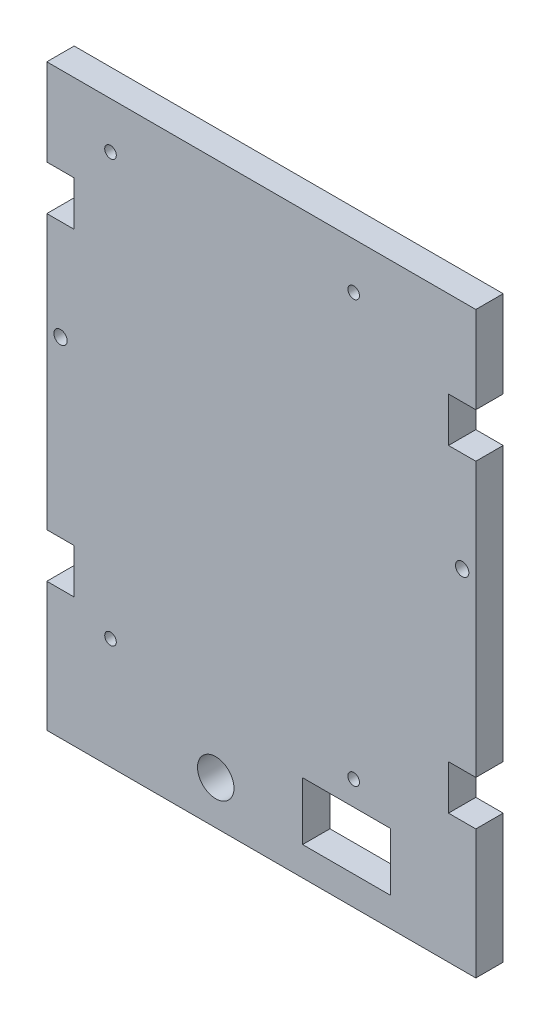
SolidWorks part; units mm, degrees
ref_plane "Front Plane" through (0, 0, 0) normal (0, 0, 1) x (1, 0, 0)
ref_plane "Top Plane" through (0, 0, 0) normal (0, 1, 0) x (1, 0, 0)
ref_plane "Right Plane" through (0, 0, 0) normal (1, 0, 0) x (0, 0, -1)
sketch "Sketch1" plane through (0, 0, 0) normal (0, 0, 1) x (1, 0, 0)
  line L1 (0, 0) -> (94.107, 0)
  line L2 (0, 0) -> (0, 127)
  line L3 (0, 127) -> (94.107, 127)
  line L4 (94.107, 0) -> (94.107, 127)
  dimension "D1" = 127
  dimension "D2" = 94.107
extrude "Boss-Extrude1" add sketch "Sketch1" along normal blind 6
sketch "Sketch2" plane through (0, 0, 6) normal (0, 0, 1) x (1, 0, 0)
  line L0 (0, 127) -> (0, 0) construction
  line L1 (0, 107.95) -> (5.9944, 107.95)
  line L2 (0, 107.95) -> (0, 98.171)
  line L3 (0, 98.171) -> (5.9944, 98.171)
  line L4 (5.9944, 107.95) -> (5.9944, 98.171)
  line L5 (94.107, 0) -> (94.107, 127) construction
  line L6 (94.107, 107.95) -> (88.1126, 107.95)
  line L7 (94.107, 107.95) -> (94.107, 98.171)
  line L8 (94.107, 98.171) -> (88.1126, 98.171)
  line L9 (88.1126, 107.95) -> (88.1126, 98.171)
  line L10 (94.107, 127) -> (0, 127) construction
  line L11 (0, 38.1) -> (5.9944, 38.1)
  line L12 (0, 38.1) -> (0, 28.321)
  line L13 (0, 28.321) -> (5.9944, 28.321)
  line L14 (5.9944, 38.1) -> (5.9944, 28.321)
  line L15 (94.107, 38.1) -> (88.1126, 38.1)
  line L16 (94.107, 38.1) -> (94.107, 28.321)
  line L17 (94.107, 28.321) -> (88.1126, 28.321)
  line L18 (88.1126, 38.1) -> (88.1126, 28.321)
  dimension "D1" = 5.9944
  dimension "D2" = 9.779
  dimension "D3" = 19.05
  dimension "D4" = 88.9
extrude "Cut-Extrude1" cut sketch "Sketch2" against normal through all
sketch "Sketch3" plane through (0, 0, 0) normal (0, 0, -1) x (-1, 0, 0)
  circle A0 centre (-67.31, 24.384) radius 1.27
  circle A1 centre (-67.31, 116.84) radius 1.27
  circle A2 centre (-13.97, 116.84) radius 1.27
  circle A3 centre (-13.97, 24.384) radius 1.27
  dimension "D1" = 2.54
extrude "Cut-Extrude2" cut sketch "Sketch3" against normal through all
sketch "Sketch4" plane through (0, 0, 6) normal (0, 0, 1) x (1, 0, 0)
  line L0 (0, 0) -> (94.107, 0) construction
  line L1 (56.1086, 19.05) -> (75.4126, 19.05)
  line L2 (56.1086, 19.05) -> (56.1086, 6.35)
  line L3 (56.1086, 6.35) -> (75.4126, 6.35)
  line L4 (75.4126, 19.05) -> (75.4126, 6.35)
  line L7 (88.1126, 38.1) -> (88.1126, 28.321) construction
  circle A0 centre (37.0586, 9.525) radius 4.0005
  dimension "D1" = 8.001
  dimension "D2" = 19.304
  dimension "D3" = 12.7
  dimension "D4" = 6.35
  dimension "D5" = 12.7
  dimension "D6" = 9.525
  dimension "D7" = 19.05
extrude "Cut-Extrude3" cut sketch "Sketch4" against normal through all
sketch "Sketch5" plane through (0, 0, 6) normal (0, 0, 1) x (1, 0, 0)
  line L0 (0, 76.2) -> (94.107, 76.2) construction
  line L1 (0, 98.171) -> (0, 38.1) construction
  line L2 (94.107, 38.1) -> (94.107, 98.171) construction
  line L3 (2.9972, 98.171) -> (2.9972, 76.2) construction
  line L4 (0, 98.171) -> (5.9944, 98.171) construction
  line L5 (91.1098, 98.171) -> (91.1098, 76.2) construction
  line L6 (88.1126, 98.171) -> (94.107, 98.171) construction
  line L7 (94.107, 127) -> (0, 127) construction
  circle A0 centre (2.9972, 76.2) radius 1.4605
  circle A1 centre (91.1098, 76.2) radius 1.4605
  dimension "D1" = 2.921
  dimension "D2" = 50.8
extrude "Cut-Extrude4" cut sketch "Sketch5" against normal through all
